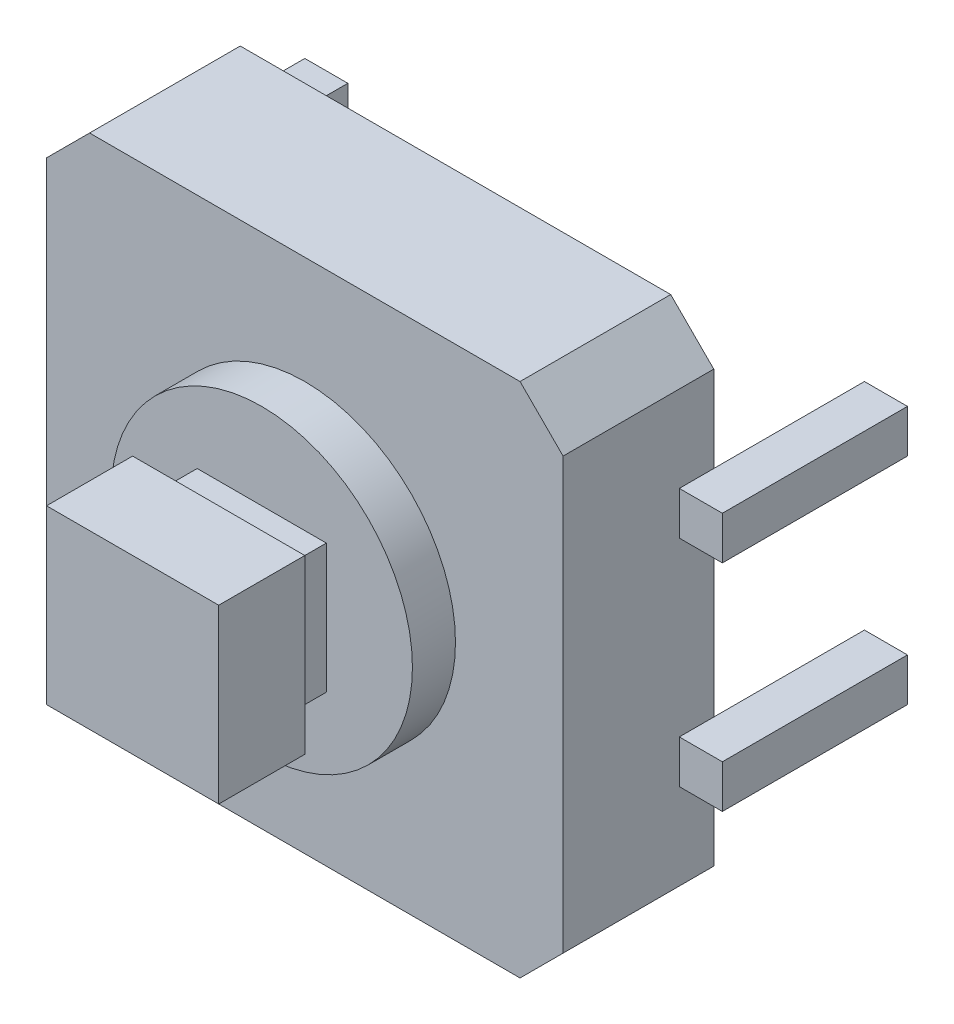
SolidWorks part; units mm, degrees
ref_plane "정면" through (0, 0, 0) normal (0, 0, 1) x (1, 0, 0)
ref_plane "윗면" through (0, 0, 0) normal (0, 1, 0) x (1, 0, 0)
ref_plane "우측면" through (0, 0, 0) normal (1, 0, 0) x (0, 0, -1)
sketch "스케치1" plane through (0, 0, 0) normal (0, 0, 1) x (1, 0, 0)
  line L1 (-6, -6) -> (6, -6)
  line L2 (-6, -6) -> (-6, 6)
  line L3 (-6, 6) -> (6, 6)
  line L4 (6, -6) -> (6, 6)
  line L5 (-6, -6) -> (6, 6) construction
  line L6 (-6, 6) -> (6, -6) construction
  point P0 (0, 0)
  dimension "D1" = 12
  dimension "D2" = 12
extrude "보스-돌출1" add sketch "스케치1" along normal blind 3.5
sketch "스케치2" plane through (0, 0, 3.5) normal (0, 0, 1) x (1, 0, 0)
  circle A0 centre (0, 0) radius 3.5
extrude "보스-돌출2" add sketch "스케치2" along normal blind 1
sketch "스케치3" plane through (0, 0, 4.5) normal (0, 0, 1) x (1, 0, 0)
  line L1 (-1.5, -1.5) -> (1.5, -1.5)
  line L2 (-1.5, -1.5) -> (-1.5, 1.5)
  line L3 (-1.5, 1.5) -> (1.5, 1.5)
  line L4 (1.5, -1.5) -> (1.5, 1.5)
  line L5 (-1.5, -1.5) -> (1.5, 1.5) construction
  line L6 (-1.5, 1.5) -> (1.5, -1.5) construction
  point P0 (0, 0)
  dimension "D1" = 3
  dimension "D2" = 3
extrude "보스-돌출3" add sketch "스케치3" along normal blind 1
sketch "스케치4" plane through (0, 0, 5.5) normal (0, 0, 1) x (1, 0, 0)
  line L1 (-2, -2) -> (2, -2)
  line L2 (-2, -2) -> (-2, 2)
  line L3 (-2, 2) -> (2, 2)
  line L4 (2, -2) -> (2, 2)
  line L5 (-2, -2) -> (2, 2) construction
  line L6 (-2, 2) -> (2, -2) construction
  point P0 (0, 0)
  dimension "D1" = 4
  dimension "D2" = 4
extrude "보스-돌출4" add sketch "스케치4" along normal blind 2
sketch "스케치5" plane through (-6, 0, 0) normal (-1, 0, 0) x (0, 0, 1)
  line L0 (0, 0) -> (2.3186, 0) construction
  line L1 (0, 6) -> (0, -6) construction
  line L2 (0.8, 3) -> (-3.5, 3)
  line L3 (0.8, 3) -> (0.8, 2)
  line L4 (0.8, 2) -> (-3.5, 2)
  line L5 (-3.5, 3) -> (-3.5, 2)
  line L6 (0.8, -2) -> (-3.5, -2)
  line L7 (-3.5, -3) -> (-3.5, -2)
  line L8 (0.8, -3) -> (-3.5, -3)
  line L9 (0.8, -3) -> (0.8, -2)
  line M10 (0, 6) -> (0, -6)
  dimension "D1" = 0.8
  dimension "D2" = 1
  dimension "D3" = 4.3
  dimension "D4" = 2
extrude "보스-돌출5" add sketch "스케치5" along normal blind 1 contours L8 L6 L7 M10 | L3 L2 L5 L4
sketch "스케치7" plane through (6, 0, 0) normal (1, 0, 0) x (0, 0, -1)
  line L0 (0, 0) -> (-2.745, 0) construction
  line L2 (3.5, 3) -> (-0.8, 3)
  line L3 (3.5, 3) -> (3.5, 2)
  line L4 (3.5, 2) -> (-0.8, 2)
  line L5 (-0.8, 3) -> (-0.8, 2)
  line L6 (3.5, -2) -> (-0.8, -2)
  line L7 (3.5, -2) -> (3.5, -3)
  line L8 (3.5, -3) -> (-0.8, -3)
  line L9 (-0.8, -2) -> (-0.8, -3)
  dimension "D1" = 1
  dimension "D2" = 4.3
  dimension "D3" = 1
  dimension "D4" = 4.3
extrude "보스-돌출6" add sketch "스케치7" along normal blind 1
chamfer "모따기1" distance 1 4 edges at (6, -6, 1.75) (6, 6, 1.75) (-6, 6, 1.75) (-6, -6, 1.75)
